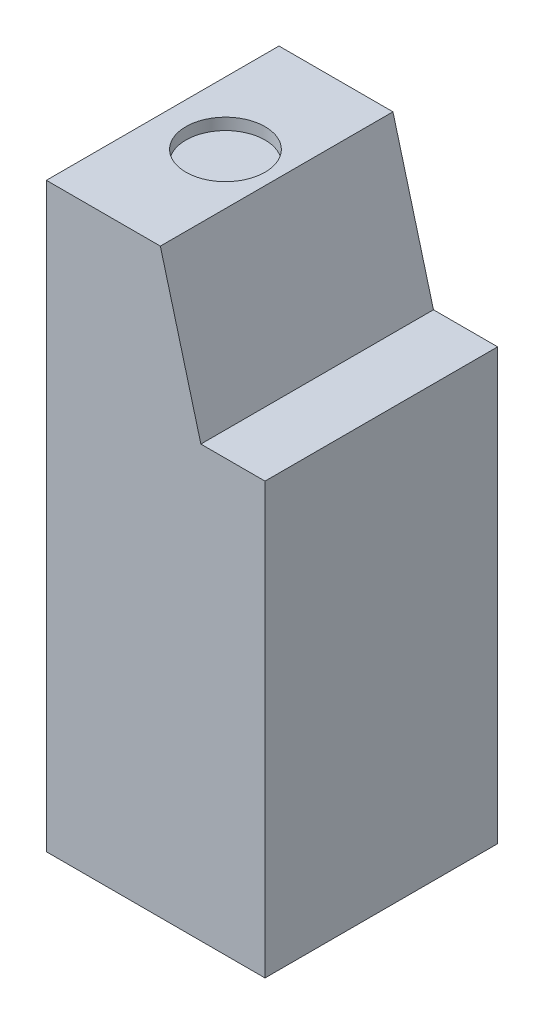
SolidWorks part; units mm, degrees
ref_plane "Front" through (0, 0, 0) normal (0, 0, 1) x (1, 0, 0)
ref_plane "Top" through (0, 0, 0) normal (0, 1, 0) x (1, 0, 0)
ref_plane "Right" through (0, 0, 0) normal (1, 0, 0) x (0, 0, -1)
sketch "Base Sketch" plane through (0, 0, 0) normal (0, 0, 1) x (1, 0, 0)
  line L1 (0, 0) -> (0, 18.5)
  line L2 (0, 18.5) -> (-9.4, 18.5)
  line L5 (-9.4, 18.5) -> (-9.4, 0)
  line L6 (-9.4, 0) -> (0, 0)
  dimension "D1" = 9.4
  dimension "D2" = 18.5
extrude "Base" add sketch "Base Sketch" along normal mid plane 10
sketch "Base Top Sketch" plane through (0, 0, 0) normal (0, 0, 1) x (1, 0, 0)
  line L0 (0, 18.5) -> (-9.4, 18.5) construction
  line L1 (-2.7583, 18.5) -> (-9.4, 18.5)
  line L2 (-9.4, 18.5) -> (-9.4, 25)
  line L3 (-9.4, 25) -> (-4.5, 25)
  line L4 (-4.5, 25) -> (-2.7583, 18.5)
  line L7 (0, 0) -> (0, 18.5) construction
  dimension "D1" = 4.5
  dimension "D2" = 6.5
  dimension "D3" = 105
extrude "Base Top" add sketch "Base Top Sketch" along normal mid plane 10
sketch "Man-op cutout sketch" plane through (0, 25, 0) normal (0, 1, 0) x (-1, 0, 0)
  line L2 (5.17, 0) -> (-5.17, 0) construction
  line L3 (9.4, 5) -> (9.4, -5) construction
  circle A0 centre (6.7, 0) radius 1.7
  dimension "D1" = 3.4
  dimension "D2" = 2.7
extrude "Man-op cutout" cut sketch "Man-op cutout sketch" against normal blind 0.5
